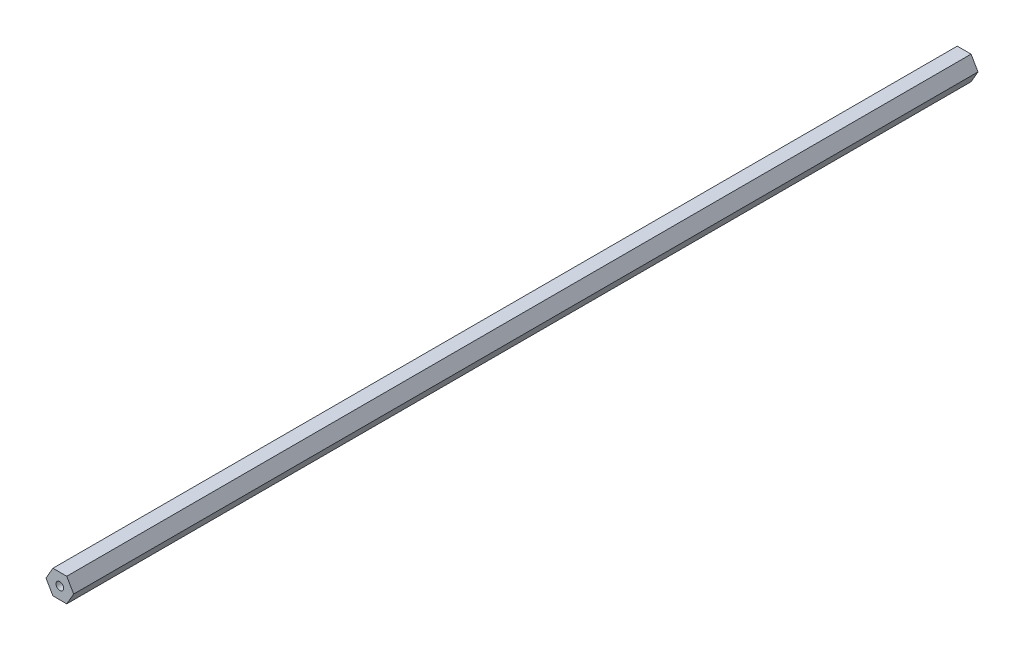
SolidWorks part; units mm, degrees
material "6061 Alloy"
ref_plane "Front Plane" through (0, 0, 0) normal (0, 0, 1) x (1, 0, 0)
ref_plane "Top Plane" through (0, 0, 0) normal (0, 1, 0) x (1, 0, 0)
ref_plane "Right Plane" through (0, 0, 0) normal (1, 0, 0) x (0, 0, -1)
sketch "Sketch1" plane through (0, 0, 0) normal (0, 0, 1) x (1, 0, 0)
  line L1 (7.3323, 0) -> (3.6662, 6.35)
  line L2 (3.6662, 6.35) -> (-3.6662, 6.35)
  line L3 (-3.6662, 6.35) -> (-7.3323, 0)
  line L4 (-7.3323, 0) -> (-3.6662, -6.35)
  line L5 (-3.6662, -6.35) -> (3.6662, -6.35)
  line L6 (3.6662, -6.35) -> (7.3323, 0)
  circle A0 centre (0, 0) radius 6.35 construction
  circle A1 centre (0, 0) radius 2.0193
  dimension "D1" = 12.7
  dimension "D2" = 4.0386
extrude "Boss-Extrude1" add sketch "Sketch1" along normal blind 479.425
